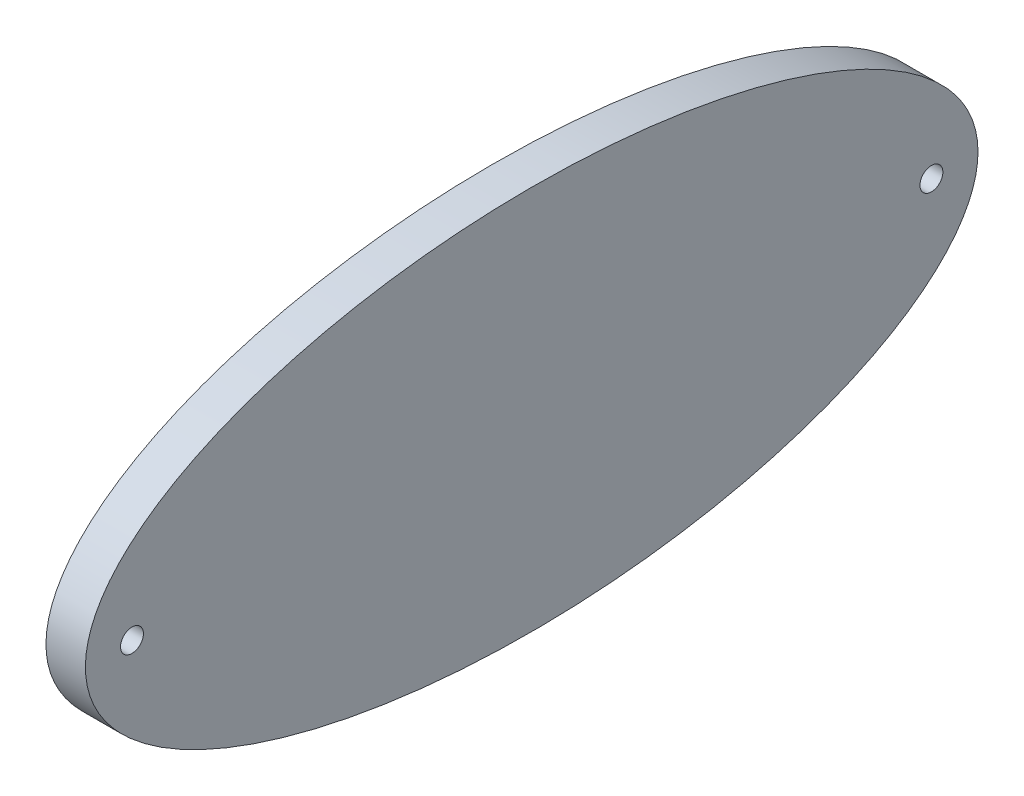
SolidWorks part; units mm, degrees
ref_plane "Front Plane" through (0, 0, 0) normal (0, 0, 1) x (1, 0, 0)
ref_plane "Top Plane" through (0, 0, 0) normal (0, 1, 0) x (1, 0, 0)
ref_plane "Right Plane" through (0, 0, 0) normal (1, 0, 0) x (0, 0, -1)
sketch "Sketch1" plane through (0, 0, 0) normal (1, 0, 0) x (0, 0, -1)
  circle A0 centre (-51.5, 0) radius 1.4732
  circle A1 centre (51.5, 0) radius 1.4732
  ellipse E0 centre (0, 0) end of major axis (57.5, 0) minor radius 24.8
  dimension "D3" = 2.9464
  dimension "D4" = 2.9464
  dimension "D1" = 49.6
  dimension "D2" = 115
  dimension "D5" = 6
  dimension "D6" = 6
extrude "Boss-Extrude1" add sketch "Sketch1" along normal blind 5.08
